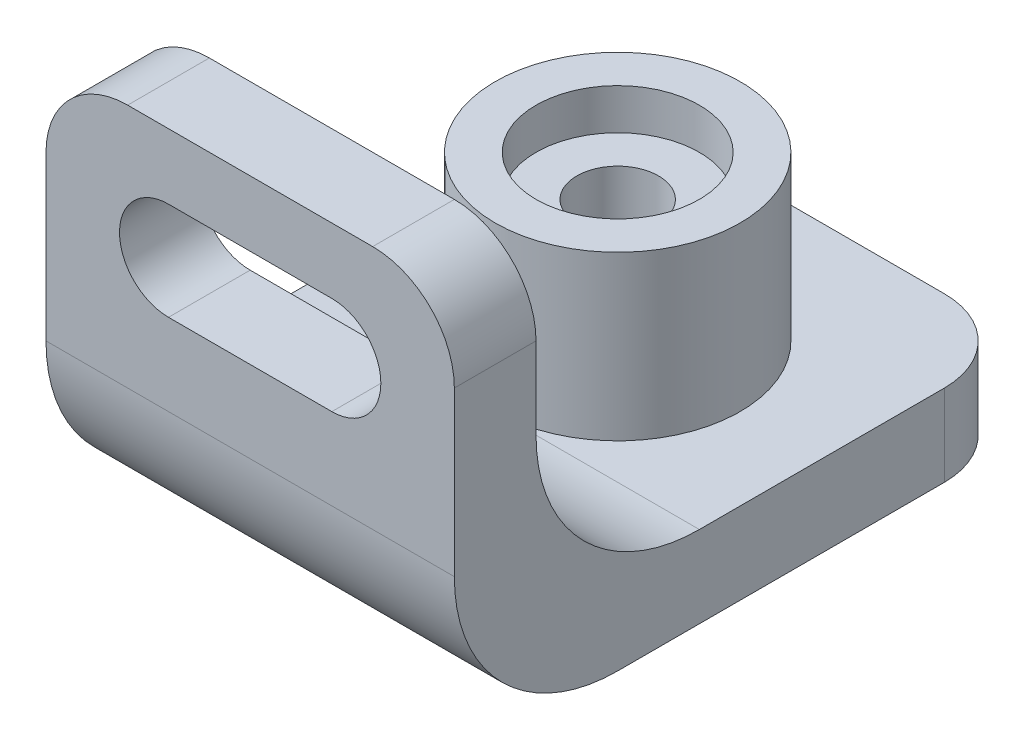
SolidWorks part; units mm, degrees
ref_plane "Alzado" through (0, 0, 0) normal (0, 0, 1) x (1, 0, 0)
ref_plane "Planta" through (0, 0, 0) normal (0, 1, 0) x (1, 0, 0)
ref_plane "Vista lateral" through (0, 0, 0) normal (1, 0, 0) x (0, 0, -1)
sketch "Croquis1" plane through (0, 0, 0) normal (1, 0, 0) x (0, 0, -1)
  line L0 (-33.6842, 31.6268) -> (-33.6842, 1.6268)
  line L1 (-13.6842, -18.3732) -> (36.3158, -18.3732)
  line L2 (-33.6842, 31.6268) -> (-23.6842, 31.6268)
  line L3 (-23.6842, 31.6268) -> (-23.6842, 11.6268)
  line L4 (-3.6842, -8.3732) -> (36.3158, -8.3732)
  line L5 (36.3158, -8.3732) -> (36.3158, -18.3732)
  arc A0 (-13.6842, -18.3732) -> (-33.6842, 1.6268) centre (-13.6842, 1.6268) cw
  arc A1 (-3.6842, -8.3732) -> (-23.6842, 11.6268) centre (-3.6842, 11.6268) cw
  point P5 (-33.6842, -18.3732)
  dimension "D3" = 20
  dimension "D7" = 20
  dimension "D1" = 50
  dimension "D2" = 70
  dimension "D4" = 10
  dimension "D5" = 30
  dimension "D6" = 10
extrude "Saliente-Extruir1" add sketch "Croquis1" along normal blind 50
sketch "Croquis2" plane through (0, 0, 23.6842) normal (0, 0, -1) x (-1, 0, 0)
  line L0 (-50, 31.6268) -> (0, 31.6268) construction
  line L2 (-35, 23.6268) -> (-15, 23.6268)
  line L4 (-35, 11.6268) -> (-15, 11.6268)
  arc A2 (-15, 11.6268) -> (-15, 23.6268) centre (-15, 17.6268) ccw
  arc A3 (-35, 23.6268) -> (-35, 11.6268) centre (-35, 17.6268) ccw
  dimension "D1" = 20
  dimension "D3" = 8
  dimension "D4" = 12
extrude "Cortar-Extruir1" cut sketch "Croquis2" against normal through all
fillet "Redondeo1" radius 10 1 edges at (50, 31.6268, 28.6842)
fillet "Redondeo2" radius 10 1 edges at (0, 31.6268, 28.6842)
fillet "Redondeo3" radius 10 1 edges at (50, -13.3732, -36.3158)
fillet "Redondeo4" radius 10 1 edges at (0, -13.3732, -36.3158)
sketch "Croquis5" plane through (0, -8.3732, 0) normal (0, 1, 0) x (1, 0, 0)
  line L0 (25, 36.3158) -> (25, 11.3158) construction
  line L1 (40, 36.3158) -> (10, 36.3158) construction
  circle A0 centre (25, 11.3158) radius 15
  dimension "D2" = 30
  dimension "D1" = 25
extrude "Saliente-Extruir5" add sketch "Croquis5" along normal blind 20 contours A0
sketch "Croquis7" plane through (0, 11.6268, 0) normal (0, 1, 0) x (1, 0, 0)
  circle A0 centre (25, 11.3158) radius 10
  dimension "D1" = 20
extrude "Cortar-Extruir3" cut sketch "Croquis7" against normal blind 5
sketch "Croquis9" plane through (0, 6.6268, 0) normal (0, 1, 0) x (1, 0, 0)
  circle A0 centre (25, 11.3158) radius 5
  dimension "D1" = 10
extrude "Cortar-Extruir4" cut sketch "Croquis9" against normal blind 15
